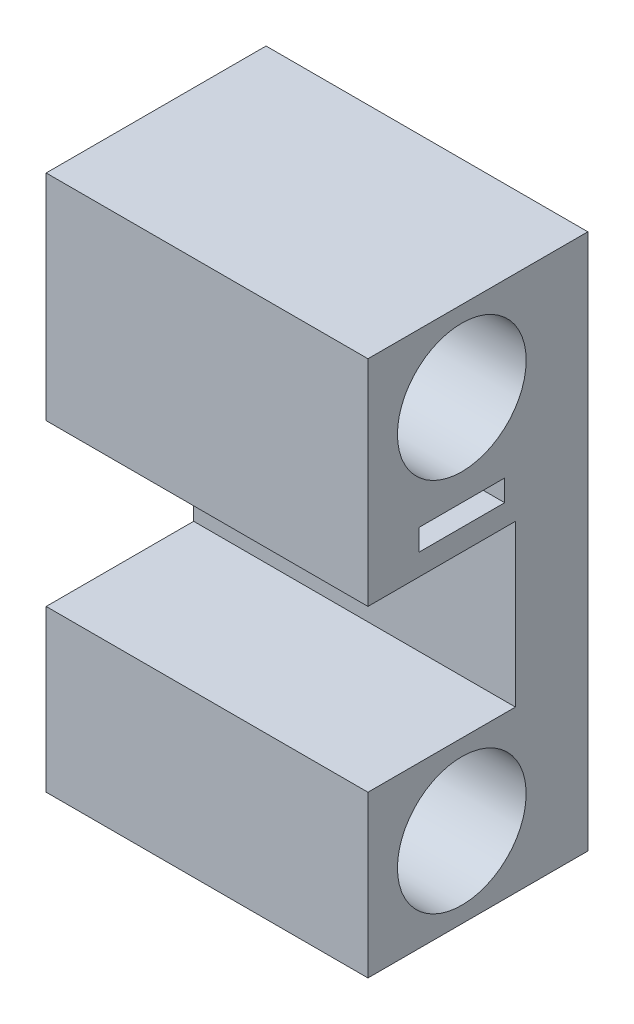
SolidWorks part; units mm, degrees
ref_plane "Front Plane" through (0, 0, 0) normal (0, 0, 1) x (1, 0, 0)
ref_plane "Top Plane" through (0, 0, 0) normal (0, 1, 0) x (1, 0, 0)
ref_plane "Right Plane" through (0, 0, 0) normal (1, 0, 0) x (0, 0, -1)
sketch "Sketch1" plane through (0, 0, 0) normal (0, 0, 1) x (1, 0, 0)
  line L1 (-30, -50) -> (30, -50)
  line L2 (-30, -50) -> (-30, 50)
  line L3 (-30, 50) -> (30, 50)
  line L4 (30, -50) -> (30, 50)
  line L5 (-30, -50) -> (30, 50) construction
  line L6 (-30, 50) -> (30, -50) construction
  point P0 (0, 0)
extrude "Boss-Extrude1" add sketch "Sketch1" along normal blind 35
sketch "Sketch3" plane through (30, 0, 0) normal (1, 0, 0) x (0, 0, -1)
  line L0 (-35, 18) -> (0, 18) construction
  line L1 (-35, -50) -> (-35, 50) construction
  line L2 (0, -50) -> (0, 50) construction
  line L5 (-25.5, 14) -> (-9.5, 14)
  line L6 (-25.5, 14) -> (-25.5, 18)
  line L7 (-25.5, 18) -> (-9.5, 18)
  line L8 (-9.5, 14) -> (-9.5, 18)
  line L9 (-25.5, 14) -> (-9.5, 18) construction
  line L10 (-25.5, 18) -> (-9.5, 14) construction
  circle A1 centre (-17.5, 35) radius 12
  circle A2 centre (-17.5, -35) radius 12
  point P6 (0, 0)
  point P7 (0, 0)
extrude "Cut-Extrude1" cut sketch "Sketch3" against normal through all both and the other way through all
sketch "Sketch4" plane through (30, 0, 0) normal (1, 0, 0) x (0, 0, -1)
  line L1 (-35, -50) -> (-35, 50) construction
  line L2 (-35, 10) -> (-7.5, 10)
  line L3 (-7.5, 10) -> (-7.5, -20)
  line L4 (-7.5, -20) -> (-35, -20)
  line L5 (-35, -20) -> (-35, 10)
extrude "Cut-Extrude2" cut sketch "Sketch4" against normal through all both and the other way through all
sketch "Sketch5" plane through (0, 10, 0) normal (0, -1, 0) x (1, 0, 0)
  line L5 (-18, 20.5698) -> (-6, 20.5698) construction
  circle A4 centre (-18, 20.5698) radius 1.5
  circle A5 centre (-6, 20.5698) radius 1.5
  circle A6 centre (6, 20.5698) radius 1.5
  circle A7 centre (18, 20.5698) radius 1.5
  dimension "D1" = 4
  dimension "D2" = 12
extrude "Cut-Extrude3" cut sketch "Sketch5" against normal blind 12
sketch "Sketch6" plane through (0, 10, 0) normal (0, -1, 0) x (1, 0, 0)
  circle A1 centre (-18, 20.5698) radius 2.75
  circle A2 centre (-6, 20.5698) radius 2.75
  circle A3 centre (6, 20.5698) radius 2.75
  circle A4 centre (18, 20.5698) radius 2.75
extrude "Cut-Extrude4" cut sketch "Sketch6" against normal blind 2
sketch "Sketch7" plane through (0, 0, 0) normal (0, 0, -1) x (-1, 0, 0)
  line L1 (-30, 50) -> (30, 50)
  line L2 (-30, 50) -> (-30, -50)
  line L3 (-30, -50) -> (30, -50)
  line L4 (30, 50) -> (30, -50)
extrude "Boss-Extrude2" add sketch "Sketch7" along normal blind 6
sketch "Sketch9" plane through (0, 0, -6) normal (0, 0, -1) x (-1, 0, 0)
  line L0 (0, 51.9054) -> (0, -53.4321) construction
  line L1 (-28.6746, 0) -> (57.9616, 0) construction
  line L3 (30, -50) -> (30, 50) construction
  line L5 (-20, 20) -> (30, 20) construction
  line L7 (-20, -20) -> (30, -20) construction
  line L8 (30, 20) -> (30, -20) construction
  line L9 (-20, 20) -> (-20, -20)
  circle A0 centre (-12.5, 12.5) radius 1.5
  circle A1 centre (-12.5, -12.5) radius 1.5
  circle A2 centre (22.5, -12.5) radius 1.5
  circle A3 centre (22.5, 12.5) radius 1.5
  point P5 (-20, 0)
  point P11 (-20, 0)
  point P14 (30, 0)
sketch "Sketch11" plane through (-30, 0, 0) normal (-1, 0, 0) x (0, 0, 1)
  line L4 (-4.5, -20) -> (-1.5, -20)
  line L5 (-4.5, -20) -> (-4.5, 20)
  line L6 (-4.5, 20) -> (-1.5, 20)
  line L7 (-1.5, -20) -> (-1.5, 20)
  line L8 (-4.5, -20) -> (-1.5, 20) construction
  line L9 (-4.5, 20) -> (-1.5, -20) construction
  point P7 (-3, 0)
  point P8 (-3, 0)
extrude "Cut-Extrude8" cut sketch "Sketch11" against normal blind 50 contours L6 L7 L4 L5
extrude "Cut-Extrude9" cut sketch "Sketch9" against normal blind 8 contours A0 | A3 | A2 | A1
sketch "Sketch12" plane through (0, 0, -6) normal (0, 0, -1) x (-1, 0, 0)
  circle A0 centre (-12.5, 12.5) radius 2.85
  circle A1 centre (22.5, 12.5) radius 2.85
  circle A2 centre (22.5, -12.5) radius 2.85
  circle A3 centre (-12.5, -12.5) radius 2.85
extrude "Cut-Extrude10" cut sketch "Sketch12" against normal blind 1
